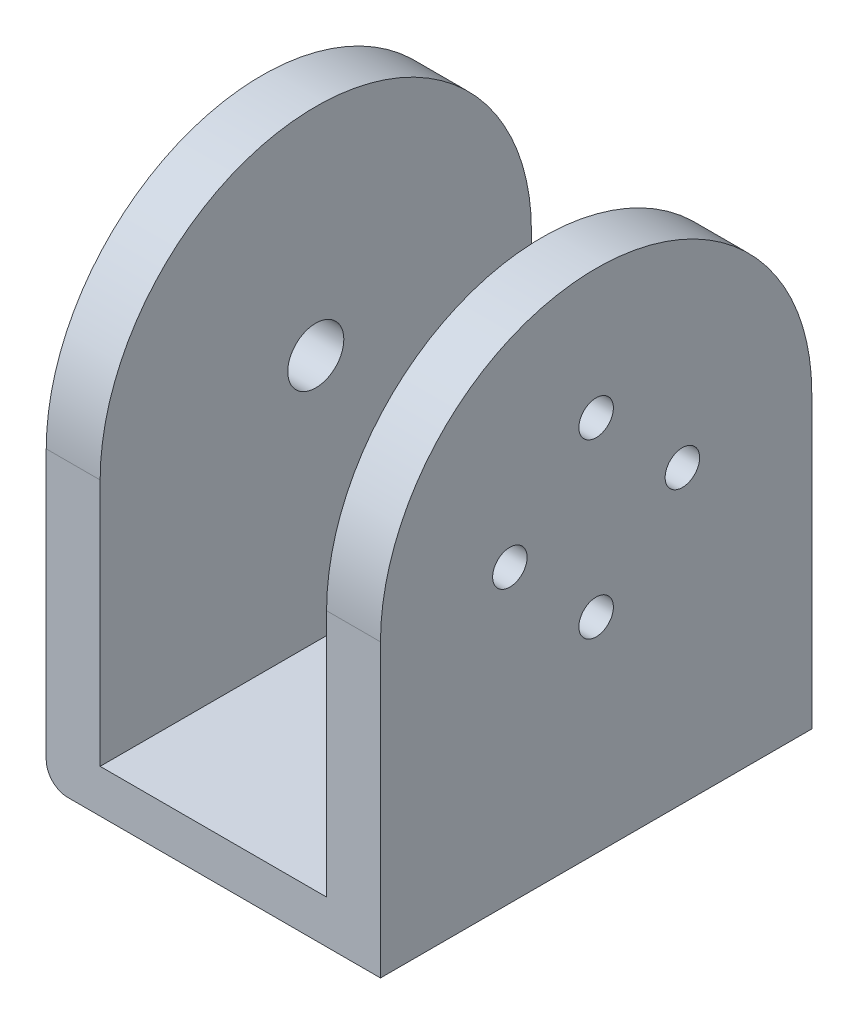
SolidWorks part; units mm, degrees
ref_plane "Front Plane" through (0, 0, 0) normal (0, 0, 1) x (1, 0, 0)
ref_plane "Top Plane" through (0, 0, 0) normal (0, 1, 0) x (1, 0, 0)
ref_plane "Right Plane" through (0, 0, 0) normal (1, 0, 0) x (0, 0, -1)
sketch "Sketch1" plane through (0, 0, 0) normal (0, 1, 0) x (1, 0, 0)
  line L1 (-23, 20) -> (23, 20)
  line L2 (-23, 20) -> (-23, -20)
  line L3 (-23, -20) -> (23, -20)
  line L4 (23, 20) -> (23, -20)
  line L5 (-23, 20) -> (23, -20) construction
  line L6 (-23, -20) -> (23, 20) construction
  point P0 (0, 0)
  dimension "D1" = 46
  dimension "D2" = 40
extrude "Boss-Extrude1" add sketch "Sketch1" along normal blind 4
sketch "Sketch2" plane through (-23, 0, 0) normal (-1, 0, 0) x (0, 0, 1)
  line L0 (-20, 49) -> (20, 49)
  line L1 (20, 4) -> (-20, 4)
  line L2 (20, 4) -> (20, 49)
  line L4 (-20, 4) -> (-20, 49)
  dimension "D2" = 45
extrude "Boss-Extrude2" add sketch "Sketch2" against normal blind 5 contours L2 L0 L4 L1
sketch "Sketch3" plane through (23, 0, 0) normal (1, 0, 0) x (0, 0, -1)
  line L2 (-20, 27) -> (-20, 2)
  line L3 (-20, 2) -> (20, 2)
  line L4 (20, 27) -> (20, 2)
  arc A0 (20, 27) -> (-20, 27) centre (0, 27) ccw
  dimension "D1" = 20
  dimension "D2" = 25
extrude "Boss-Extrude3" add sketch "Sketch3" against normal blind 20
sketch "Sketch6" plane through (0, 4, 0) normal (0, 1, 0) x (1, 0, 0)
  circle A0 centre (0, 0) radius 2.9
  circle A1 centre (-4.99, 4.99) radius 1.55
  circle A2 centre (4.99, 4.99) radius 1.4
  circle A3 centre (-4.99, -4.98) radius 1.55
  circle A4 centre (4.99, -4.98) radius 1.4
  dimension "D1" = 5.8
  dimension "D4" = 3.1
  dimension "D5" = 2.8
  dimension "D7" = 3.1
  dimension "D8" = 2.8
  dimension "D2" = 4.99
  dimension "D3" = 4.99
  dimension "D6" = 4.99
  dimension "D9" = 9.97
extrude "Cut-Extrude2" cut sketch "Sketch6" against normal blind 9
fillet "Fillet1" radius 2 1 edges at (23, 0, 0)
fillet "Fillet2" radius 2 1 edges at (-23, 0, 0)
sketch "Sketch11" plane through (-23, 0, 0) normal (-1, 0, 0) x (0, 0, 1)
  line L0 (20, 27) -> (-20, 27)
  line L1 (-20, 27) -> (-20, 47)
  line L2 (-20, 47) -> (0, 47)
  line L3 (0, 47) -> (20, 47)
  line L4 (20, 47) -> (20, 27)
  arc A0 (20, 27) -> (-20, 27) centre (0, 27) ccw
  arc A1 (-20, 27) -> (0, 47) centre (0, 27) cw
  arc A2 (20, 27) -> (0, 47) centre (0, 27) ccw
  line M10 (-20, 49) -> (-20, 2)
  line M12 (20, 2) -> (20, 49)
  line M13 (20, 49) -> (-20, 49)
extrude "Cut-Extrude4" cut sketch "Sketch11" against normal blind 10 contours A0 M13 M10 | A0 M12 M13
sketch "Sketch12" plane through (0, 49, 0) normal (0, 1, 0) x (1, 0, 0)
  line L1 (-23, 20) -> (-18, 20)
  line L2 (-23, 20) -> (-23, -20)
  line L3 (-23, -20) -> (-18, -20)
  line L4 (-18, 20) -> (-18, -20)
extrude "Cut-Extrude5" cut sketch "Sketch12" against normal up to vertex (45 mm away)
sketch "Çizim1" plane through (23, 0, 0) normal (1, 0, 0) x (0, 0, -1)
  circle A1 centre (8, 27) radius 1.6
  circle A2 centre (0, 35) radius 1.6
  circle A3 centre (-8, 27) radius 1.6
  circle A4 centre (0, 19) radius 1.6
  point P3 (8, 27)
  point P15 (0, 27)
  dimension "D3" = 3.2
  dimension "D4" = 4
extrude "Kes-Ekstrüzyon1" cut sketch "Çizim1" against normal blind 25
sketch "Çizim2" plane through (-23, 0, 0) normal (-1, 0, 0) x (0, 0, 1)
  circle A0 centre (0, 27) radius 2.6
  dimension "D1" = 5.2
extrude "Kes-Ekstrüzyon2" cut sketch "Çizim2" against normal blind 10
sketch "Sketch18" plane through (23, 0, 0) normal (1, 0, 0) x (0, 0, -1)
  line L3 (-20, 27) -> (-20, 2)
  line L4 (-20, 2) -> (20, 2)
  line L5 (20, 2) -> (20, 27)
  line L6 (-20, 27) -> (-20, 2)
  line L7 (-20, 2) -> (20, 2)
  line L8 (20, 2) -> (20, 27)
  arc A1 (20, 27) -> (-20, 27) centre (0, 27) ccw
  arc A3 (20, 27) -> (-20, 27) centre (0, 27) ccw
  dimension "D1" = 0
extrude "Cut-Extrude11" cut sketch "Sketch18" against normal blind 15
sketch "Sketch19" plane through (0, 2, 0) normal (0, 1, 0) x (1, 0, 0)
  line L1 (8, 20) -> (23, 20)
  line L2 (8, 20) -> (8, -20)
  line L3 (8, -20) -> (23, -20)
  line L4 (23, 20) -> (23, -20)
extrude "Cut-Extrude12" cut sketch "Sketch19" against normal blind 15
sketch "Sketch20" plane through (0, 0, 0) normal (0, -1, 0) x (-1, 0, 0)
  circle A0 centre (-4.99, -4.98) radius 1.4
  circle A1 centre (-4.99, 4.99) radius 1.4
  circle A2 centre (0, 0) radius 2.9
extrude "Boss-Extrude4" add sketch "Sketch20" along a picked direction on the side against the normal blind 4 contours A2 | A1 | A0
